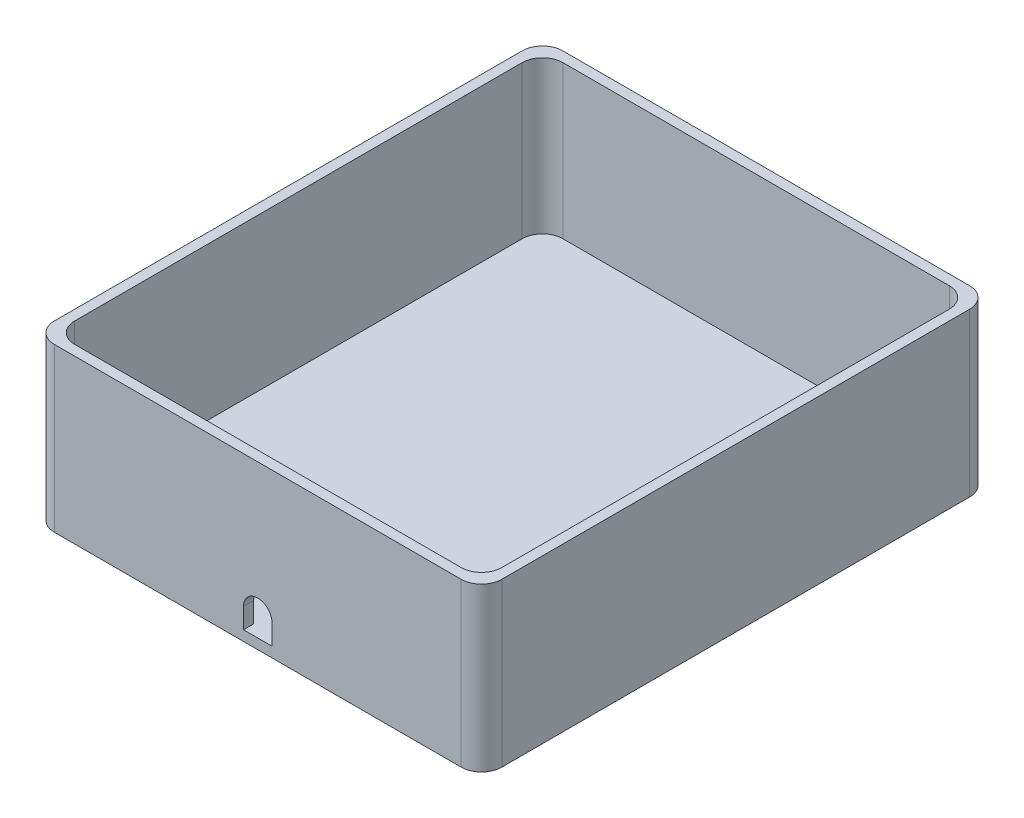
SolidWorks part; units mm, degrees
ref_plane "Front Plane" through (0, 0, 0) normal (0, 0, 1) x (1, 0, 0)
ref_plane "Top Plane" through (0, 0, 0) normal (0, 1, 0) x (1, 0, 0)
ref_plane "Right Plane" through (0, 0, 0) normal (1, 0, 0) x (0, 0, -1)
sketch "Sketch2" plane through (0, 0, 0) normal (0, 1, 0) x (1, 0, 0)
  line L1 (110, -125) -> (-110, -125)
  line L2 (110, -125) -> (110, 125)
  line L3 (110, 125) -> (-110, 125)
  line L4 (-110, -125) -> (-110, 125)
  line L5 (110, -125) -> (-110, 125) construction
  line L6 (110, 125) -> (-110, -125) construction
  point P0 (0, 0)
  dimension "D1" = 250
  dimension "D2" = 220
extrude "Boss-Extrude2" add sketch "Sketch2" along normal blind 80
sketch "Sketch3" plane through (0, 80, 0) normal (0, 1, 0) x (1, 0, 0)
  line L0 (-110, 125) -> (-110, -125) construction
  line L5 (105, -120) -> (-105, -120)
  line L6 (105, -120) -> (105, 120)
  line L7 (105, 120) -> (-105, 120)
  line L8 (-105, -120) -> (-105, 120)
  line L9 (105, -120) -> (-105, 120) construction
  line L10 (105, 120) -> (-105, -120) construction
  line L11 (110, 125) -> (-110, 125) construction
  point P0 (0, 0)
  dimension "D1" = 5
  dimension "D2" = 5
extrude "Cut-Extrude1" cut sketch "Sketch3" against normal blind 75
fillet "Fillet1" radius 10 8 edges at (-105, 42.5, 120) (105, 42.5, 120) (-110, 40, -125) (105, 42.5, -120) (110, 40, -125) (-105, 42.5, -120) (-110, 40, 125) (110, 40, 125)
sketch "Sketch4" plane through (0, 0, 125) normal (0, 0, 1) x (1, 0, 0)
  line L2 (-100, 80) -> (-100, 0) construction
  line L3 (-7, 5) -> (-7, 15)
  line L4 (7, 5) -> (7, 15)
  line L5 (-7, 5) -> (7, 5)
  line L6 (-100, 0) -> (100, 0) construction
  line L7 (100, 0) -> (100, 80) construction
  arc A1 (7, 15) -> (-7, 15) centre (0, 15) ccw
  point P2 (-7, 10)
  point P6 (0, 0)
  dimension "D3" = 7
  dimension "D1" = 5
  dimension "D2" = 15
  dimension "D4" = 93
  dimension "D5" = 93
  dimension "D6" = 10
extrude "Cut-Extrude2" cut sketch "Sketch4" against normal blind 75
